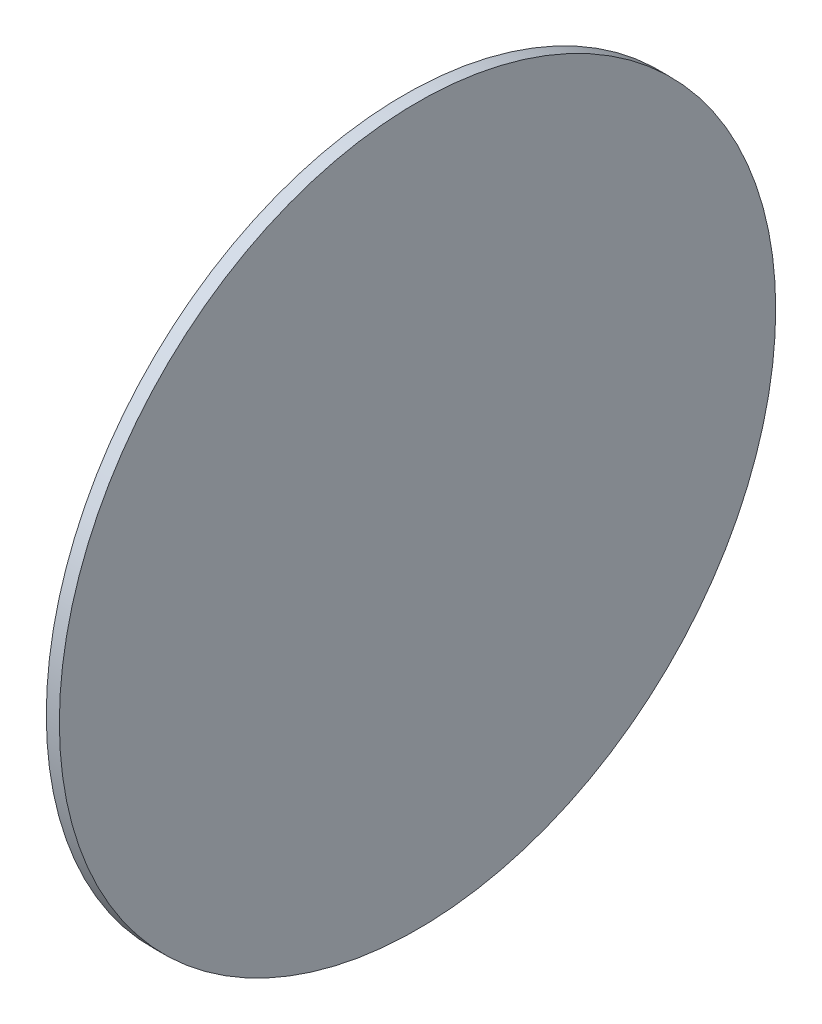
SolidWorks part; units mm, degrees
material "Gray Cast Iron (w/YS)"
ref_plane "X-Y Datum" through (0, 0, 0) normal (0, 0, 1) x (1, 0, 0)
ref_plane "X-Z Datum" through (0, 0, 0) normal (0, 1, 0) x (1, 0, 0)
ref_plane "Y-Z Datum" through (0, 0, 0) normal (1, 0, 0) x (0, 0, -1)
sketch "Sketch1" plane through (0, 0, 0) normal (1, 0, 0) x (0, 0, -1)
  circle A0 centre (0, 0) radius 130.175
  dimension "D1" = 260.35
extrude "Boss-Extrude1" add sketch "Sketch1" along normal blind 4.75
